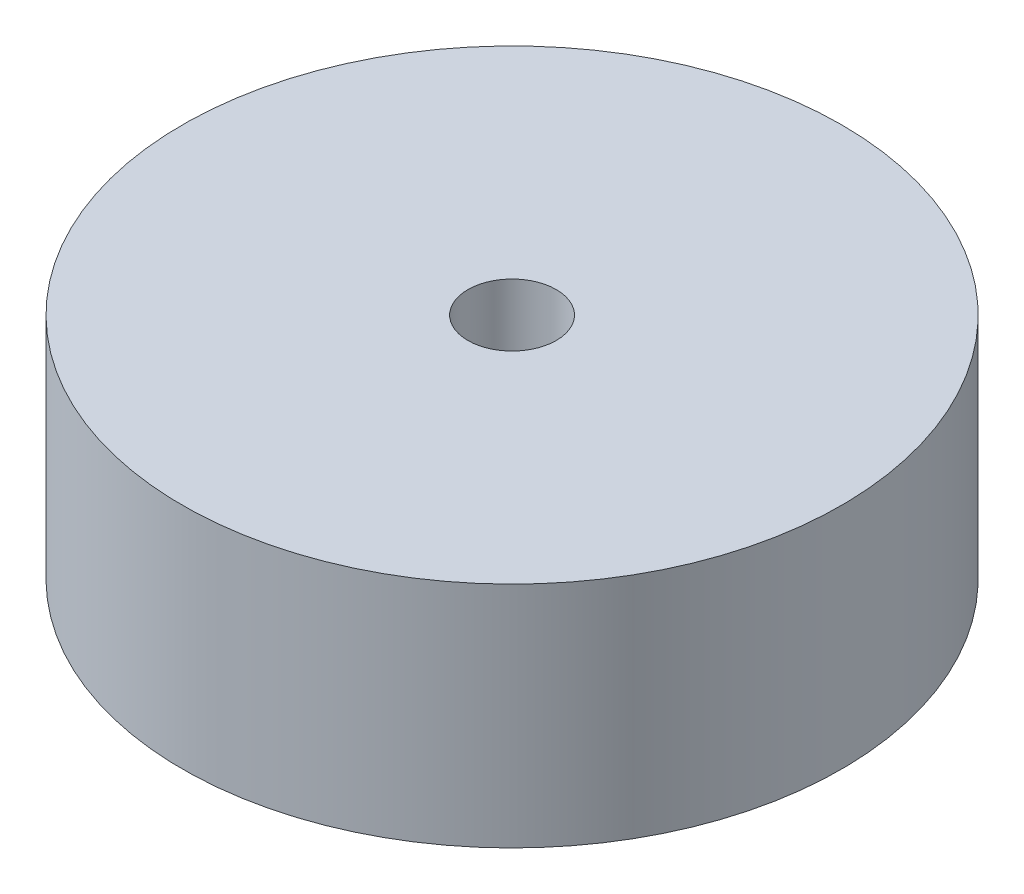
SolidWorks part; units mm, degrees
ref_plane "Front Plane" through (0, 0, 0) normal (0, 0, 1) x (1, 0, 0)
ref_plane "Top Plane" through (0, 0, 0) normal (0, 1, 0) x (1, 0, 0)
ref_plane "Right Plane" through (0, 0, 0) normal (1, 0, 0) x (0, 0, -1)
sketch "Sketch1" plane through (0, 0, 0) normal (0, 1, 0) x (1, 0, 0)
  circle A0 centre (0, 0) radius 19.05
  dimension "D1" = 38.1
extrude "Boss-Extrude1" add sketch "Sketch1" along normal blind 13.208
hole_wizard "1/4-20 Tapped Hole1" positions "Sketch2" profile "Sketch3" tap size "1/4-20" standard "ANSI Inch"
sketch "Sketch2" plane through (0, 0, 0) normal (0, -1, 0) x (-1, 0, 0)
  point P0 (0, 0)
sketch "Sketch3" plane through (0, 0, 0) normal (1, 0, 0) x (0, 0, -1)
  line L0 (0, 0) -> (0, 18.0438)
  line L1 (0, 18.0438) -> (2.5527, 16.51)
  line L2 (2.5527, 16.51) -> (2.5527, 0)
  line L5 (2.5527, 0) -> (0, 0)
  line L10 (0, 18.0438) -> (-2.5527, 16.51) construction
  line L11 (0, -6.35) -> (0, 107.95) construction
  dimension "Tap Drill Dia." = 5.1054
  dimension "Tap Drill Depth" = 16.51
  dimension "Drill Angle" = 118
cosmetic thread "Hole Thread1" parameters "D1"=12.7, "D2"=6.35
